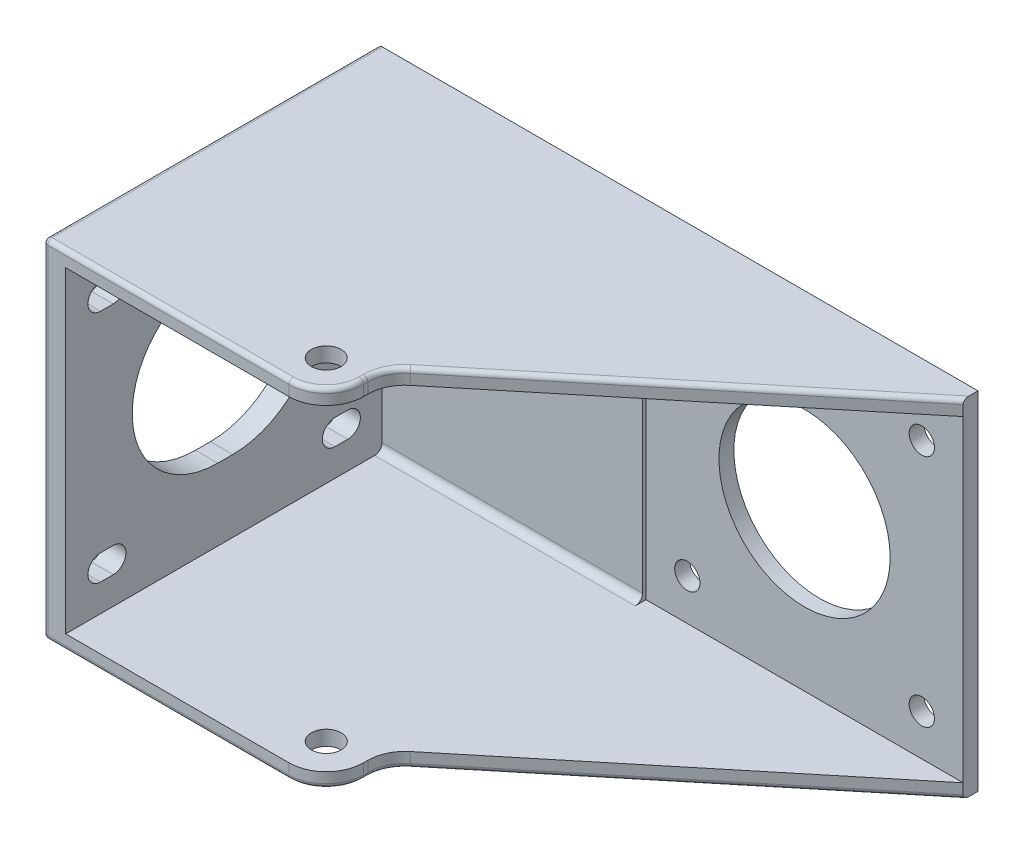
SolidWorks part; units mm, degrees
ref_plane "Front" through (0, 0, 0) normal (0, 0, 1) x (1, 0, 0)
ref_plane "Top" through (0, 0, 0) normal (0, 1, 0) x (1, 0, 0)
ref_plane "Right" through (0, 0, 0) normal (1, 0, 0) x (0, 0, -1)
sketch "Эскиз1" plane through (0, 0, 0) normal (0, 0, 1) x (1, 0, 0)
  line L1 (-15.75, -15.75) -> (15.75, -15.75) construction
  line L2 (-15.75, -15.75) -> (-15.75, 15.75) construction
  line L3 (-15.75, 15.75) -> (15.75, 15.75) construction
  line L4 (15.75, -15.75) -> (15.75, 15.75) construction
  line L5 (-15.75, -15.75) -> (15.75, 15.75) construction
  line L6 (-15.75, 15.75) -> (15.75, -15.75) construction
  line L7 (-21.3, -21.3) -> (21.3, -21.3)
  line L8 (-21.3, -21.3) -> (-21.3, 21.3)
  line L9 (-21.3, 21.3) -> (21.3, 21.3)
  line L10 (21.3, -21.3) -> (21.3, 21.3)
  line L11 (-21.3, -21.3) -> (21.3, 21.3) construction
  line L12 (-21.3, 21.3) -> (21.3, -21.3) construction
  circle A0 centre (-15.75, 15.75) radius 1.7
  circle A1 centre (15.75, 15.75) radius 1.7
  circle A2 centre (15.75, -15.75) radius 1.7
  circle A3 centre (-15.75, -15.75) radius 1.7
  circle A4 centre (0, 0) radius 11.5
  point P0 (0, 0)
  point P10 (0, 0)
  dimension "D3" = 42.6
  dimension "D5" = 23
  dimension "D1" = 31.5
  dimension "D2" = 31.5
  dimension "D4" = 42.6
extrude "Бобышка-Вытянуть1" add sketch "Эскиз1" along normal blind 2
sketch "Эскиз2" plane through (-21.3, 0, 0) normal (-1, 0, 0) x (0, 0, 1)
  line L1 (0, 21.3) -> (37, 21.3)
  line L2 (0, 21.3) -> (0, -21.3)
  line L3 (0, -21.3) -> (37, -21.3)
  line L4 (37, 21.3) -> (37, -21.3)
  dimension "D1" = 37
extrude "Бобышка-Вытянуть2" add sketch "Эскиз2" along normal blind 2
sketch "Эскиз3" plane through (0, -21.3, 0) normal (0, -1, 0) x (1, 0, 0)
  line L0 (-23.3, 0) -> (-23.3, 37)
  line L1 (-23.3, 37) -> (-21.3, 37)
  line L2 (-21.3, 37) -> (21.3, 2)
  line L3 (21.3, 2) -> (21.3, 0)
  line L4 (21.3, 0) -> (-23.3, 0)
extrude "Бобышка-Вытянуть3" add sketch "Эскиз3" along normal blind 2
sketch "Эскиз4" plane through (0, 21.3, 0) normal (0, 1, 0) x (1, 0, 0)
  line L0 (-23.3, -37) -> (-23.3, 0)
  line L1 (-23.3, 0) -> (21.3, 0)
  line L2 (21.3, 0) -> (21.3, -2)
  line L3 (21.3, -2) -> (-21.3, -37)
  line L4 (-21.3, -37) -> (-23.3, -37)
extrude "Бобышка-Вытянуть4" add sketch "Эскиз4" along normal blind 2
sketch "Sketch1" plane through (-23.3, 0, 0) normal (-1, 0, 0) x (0, 0, 1)
  line L1 (0, -23.3) -> (44.9571, -23.3)
  line L2 (0, -23.3) -> (0, 23.3)
  line L3 (0, 23.3) -> (44.9571, 23.3)
  line L4 (44.9571, -23.3) -> (44.9571, 23.3)
extrude "Boss-Extrude1" add sketch "Sketch1" along normal blind 36 and the other way blind 2
sketch "Sketch4" plane through (0, 0, 44.9571) normal (0, 0, 1) x (1, 0, 0)
  line L0 (-59.3, -23.3) -> (-59.3, 23.3) construction
  line L1 (-21.3, 21.3) -> (-56.3, 21.3)
  line L2 (-21.3, 21.3) -> (-21.3, -21.3)
  line L3 (-21.3, -21.3) -> (-56.3, -21.3)
  line L4 (-56.3, 21.3) -> (-56.3, -21.3)
  dimension "D1" = 3
extrude "Cut-Extrude2" cut sketch "Sketch4" against normal blind 42.5
sketch "Sketch5" plane through (-59.3, 0, 0) normal (-1, 0, 0) x (0, 0, 1)
  line L0 (38.5708, -14.2023) -> (40.2708, -14.2023)
  line L2 (36.8708, 15.5977) -> (40.2708, 15.5977) construction
  line L3 (40.2708, 13.8977) -> (40.2708, 15.5977) construction
  line L7 (38.5708, 13.8977) -> (40.2708, 13.8977)
  line L8 (38.5708, 17.2977) -> (40.2708, 17.2977)
  line L9 (7.0708, 17.2977) -> (8.7708, 17.2977)
  line L10 (7.0708, -14.2023) -> (8.7708, -14.2023)
  line L11 (7.0708, 13.8977) -> (8.7708, 13.8977)
  line L12 (7.0708, -17.6023) -> (8.7708, -17.6023)
  line L13 (38.5708, -17.6023) -> (40.2708, -17.6023)
  line L14 (22.5208, 11.3477) -> (24.5208, 11.3477)
  line L15 (22.5208, -11.6523) -> (24.5208, -11.6523)
  arc A0 (8.7708, 13.8977) -> (8.7708, 17.2977) centre (8.7708, 15.5977) ccw
  arc A1 (40.2708, 13.8977) -> (40.2708, 17.2977) centre (40.2708, 15.5977) ccw
  arc A2 (40.2708, -17.6023) -> (40.2708, -14.2023) centre (40.2708, -15.9023) ccw
  arc A3 (8.7708, -17.6023) -> (8.7708, -14.2023) centre (8.7708, -15.9023) ccw
  arc A5 (7.0708, 17.2977) -> (7.0708, 13.8977) centre (7.0708, 15.5977) ccw
  arc A6 (38.5708, 17.2977) -> (38.5708, 13.8977) centre (38.5708, 15.5977) ccw
  arc A7 (38.5708, -14.2023) -> (38.5708, -17.6023) centre (38.5708, -15.9023) ccw
  arc A8 (7.0708, -14.2023) -> (7.0708, -17.6023) centre (7.0708, -15.9023) ccw
  arc A9 (22.5208, 11.3477) -> (22.5208, -11.6523) centre (22.5208, -0.1523) ccw
  arc A10 (24.5208, -11.6523) -> (24.5208, 11.3477) centre (24.5208, -0.1523) ccw
  dimension "D1" = 31.5
  dimension "D2" = 31.5
extrude "Cut-Extrude3" cut sketch "Sketch5" against normal up to next
sketch "Sketch6" plane through (0, 0, 0) normal (0, 0, -1) x (-1, 0, 0)
  line L0 (59.3, 23.3) -> (59.3, -23.3) construction
  circle A0 centre (37.3, 0) radius 1.7
  dimension "D1" = 22
extrude "Cut-Extrude4" cut sketch "Sketch6" against normal up to next
sketch "Sketch7" plane through (0, 0, 2.4571) normal (0, 0, 1) x (1, 0, 0)
  circle A0 centre (-37.3, 0) radius 3
extrude "Cut-Extrude5" cut sketch "Sketch7" against normal blind 1.5
fillet "Fillet1" radius 5 4 edges at (-21.3, 22.3, 44.9571) (-21.3, -22.3, 37) (-21.3, 22.3, 37) (-21.3, -22.3, 44.9571)
fillet "Fillet2" radius 1 2 edges at (-38.8, 21.3, 2.4571) (-38.8, -21.3, 2.4571)
chamfer "Chamfer1" distance 1 angle 45 1 edges at (-34.3, 0, 0.9571)
fillet "Fillet3" radius 0.6 13 edges at (0.913, 23.3, 18.7499) (-21.3, 23.3, 39.6601) (-21.3, -23.3, 39.6601) (-42.8, 23.3, 44.9571) (-42.8, -23.3, 44.9571) (-22.7645, -23.3, 43.4926) (-22.7645, 23.3, 43.4926) (-20.8205, 23.3, 37.2266) (-20.8205, -23.3, 37.2266) (0.913, -23.3, 18.7499) (-59.3, -23.3, 22.4785) (-59.3, 0, 44.9571) (-59.3, 23.3, 22.4785)
sketch "Sketch8" plane through (0, -23.3, 0) normal (0, -1, 0) x (1, 0, 0)
  circle A0 centre (-26.3, 39.9571) radius 2
extrude "Cut-Extrude6" cut sketch "Sketch8" against normal through all
